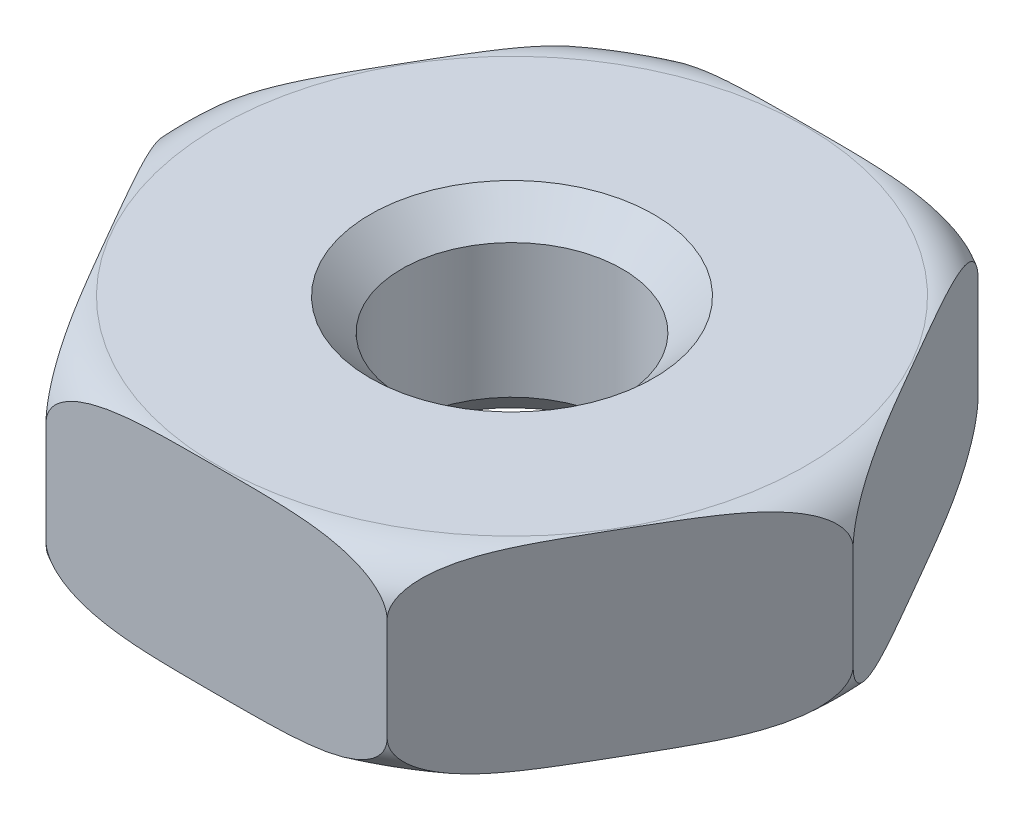
SolidWorks part; units mm, degrees
ref_plane "Front Plane" through (0, 0, 0) normal (0, 0, 1) x (1, 0, 0)
ref_plane "Top Plane" through (0, 0, 0) normal (0, 1, 0) x (1, 0, 0)
ref_plane "Right Plane" through (0, 0, 0) normal (1, 0, 0) x (0, 0, -1)
sketch "Sketch1" plane through (0, 0, 0) normal (0, 1, 0) x (1, 0, 0)
  line L1 (1.3748, 2.3813) -> (-1.3748, 2.3812)
  line L2 (-1.3748, 2.3812) -> (-2.7496, 0)
  line L3 (-2.7496, 0) -> (-1.3748, -2.3813)
  line L4 (-1.3748, -2.3813) -> (1.3748, -2.3812)
  line L5 (1.3748, -2.3812) -> (2.7496, 0)
  line L6 (2.7496, 0) -> (1.3748, 2.3813)
  circle A0 centre (0, 0) radius 2.3813 construction
  dimension "D1" = 4.7625
extrude "Boss-Extrude1" add sketch "Sketch1" along normal blind 1.5875
hole_wizard "#2-56 Tapped Hole1" positions "Sketch4" profile "Sketch3" tap size "#2-56" standard "ANSI Inch" end condition through all
sketch "Sketch4" plane through (0, 1.5875, 0) normal (0, 1, 0) x (1, 0, 0)
  point P0 (0, 0)
sketch "Sketch3" plane through (0, 1.5875, 0) normal (1, 0, 0) x (0, 0, 1)
  line L0 (0, 0) -> (0, 1.5875)
  line L1 (0, 1.5875) -> (0.889, 1.5875)
  line L2 (0.889, 1.5875) -> (0.889, 0)
  line L5 (0.889, 0) -> (0, 0)
  line L11 (0, -6.35) -> (0, 107.95) construction
  dimension "Thru Tap Drill Dia." = 1.778
  dimension "Thru Tap Drill Depth" = 1.5875
cosmetic thread "Hole Thread1" parameters "D2"=2.1844
sketch "Sketch5" plane through (0, 0, 0) normal (0, 0, 1) x (1, 0, 0)
  line L0 (0, 0) -> (0, 2.6674) construction
  line L1 (0, 0) -> (2.3686, 0)
  line L2 (0, 1.5875) -> (0, 2.0955)
  line L3 (0, 1.5875) -> (2.3686, 1.5875)
  line L4 (2.7496, 0.381) -> (2.7496, 1.2065)
  line L5 (0, 2.0955) -> (5.08, 2.0955)
  line L6 (5.08, 2.0955) -> (5.08, -0.4445)
  line L7 (5.08, -0.4445) -> (0, -0.4445)
  line L8 (0, -0.4445) -> (0, 0)
  arc A0 (2.7496, 0.381) -> (2.3686, 0) centre (2.3686, 0.381) cw
  arc A1 (2.7496, 1.2065) -> (2.3686, 1.5875) centre (2.3686, 1.2065) ccw
  point P10 (2.7496, 1.5875)
  dimension "D1" = 0.381
  dimension "D2" = 5.08
  dimension "D3" = 2.54
  dimension "D4" = 0.508
revolve "Cut-Revolve2" cut sketch "Sketch5" angle 360 about L0
chamfer "Chamfer2" distance 0.254 angle 45 2 edges at (0, 0, 0.889) (0, 1.5875, 0.889)
